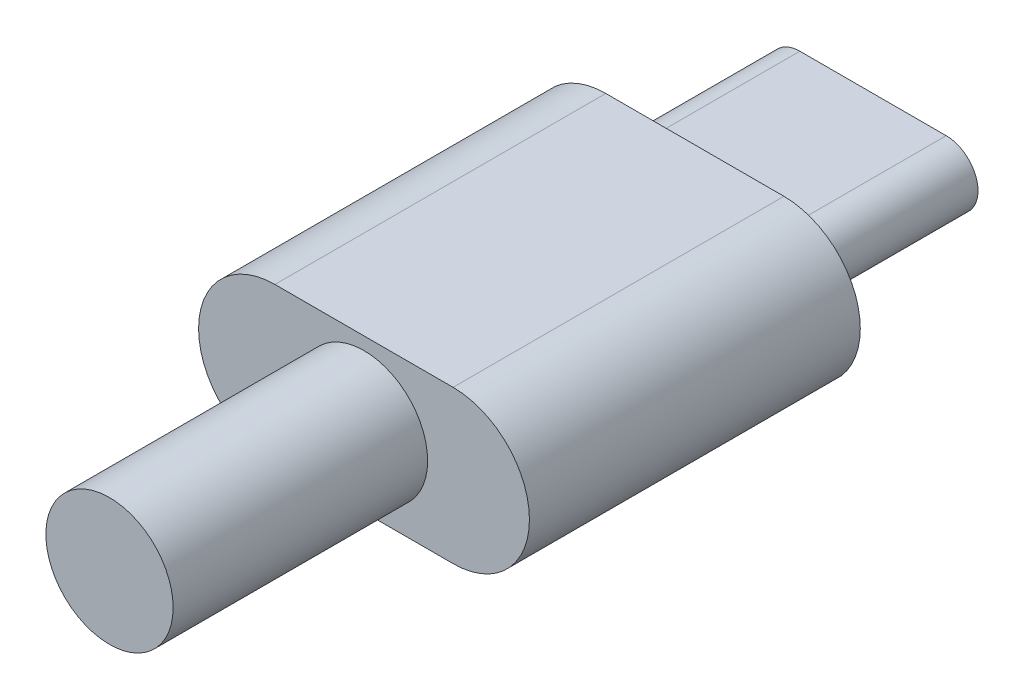
SolidWorks part; units mm, degrees
ref_plane "Front" through (0, 0, 0) normal (0, 0, 1) x (1, 0, 0)
ref_plane "Top" through (0, 0, 0) normal (0, 1, 0) x (1, 0, 0)
ref_plane "Right" through (0, 0, 0) normal (1, 0, 0) x (0, 0, -1)
sketch "Sketch1" plane through (0, 0, 0) normal (0, 0, 1) x (1, 0, 0)
  line L0 (-2.875, 0) -> (2.875, 0) construction
  line L1 (-2.875, 1.25) -> (2.875, 1.25)
  line L2 (-2.875, -1.25) -> (2.875, -1.25)
  arc A0 (-2.875, 1.25) -> (-2.875, -1.25) centre (-2.875, 0) ccw
  arc A1 (2.875, -1.25) -> (2.875, 1.25) centre (2.875, 0) ccw
  point P2 (0, 0)
  point P8 (4.125, 0)
  point P9 (-4.125, 0)
  dimension "D1" = 2.5
  dimension "D2" = 8.25
extrude "Boss-Extrude1" add sketch "Sketch1" along normal blind 7
sketch "Sketch2" plane through (0, 0, 7) normal (0, 0, 1) x (1, 0, 0)
  line L0 (-3.5, 0) -> (3.5, 0) construction
  line L1 (-3.5, 3) -> (3.5, 3)
  line L2 (-3.5, -3) -> (3.5, -3)
  arc A0 (-3.5, 3) -> (-3.5, -3) centre (-3.5, 0) ccw
  arc A1 (3.5, -3) -> (3.5, 3) centre (3.5, 0) ccw
  point P2 (0, 0)
  point P8 (-6.5, 0)
  point P9 (6.5, 0)
  dimension "D1" = 6
  dimension "D2" = 13
extrude "Boss-Extrude2" add sketch "Sketch2" along normal blind 13
sketch "Sketch3" plane through (0, 0, 20) normal (0, 0, 1) x (1, 0, 0)
  circle A0 centre (0, 0) radius 2.5
  dimension "D1" = 5
extrude "Boss-Extrude3" add sketch "Sketch3" along normal blind 10
